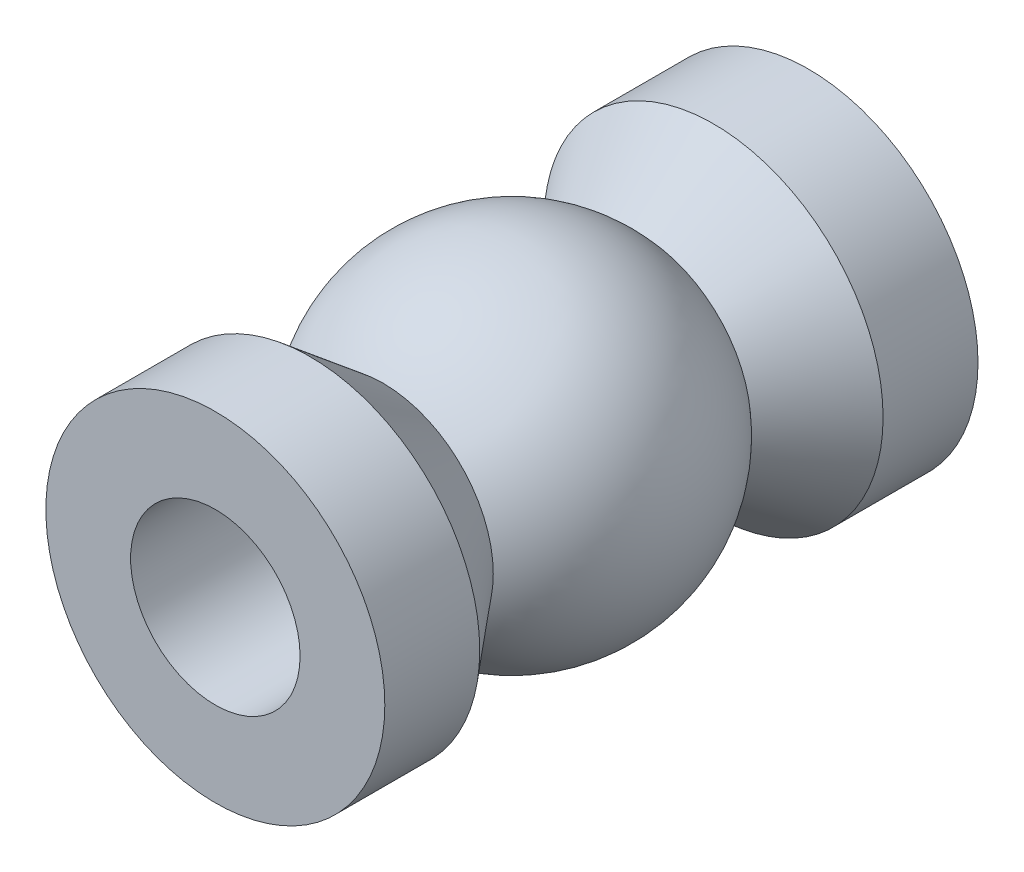
SolidWorks part; units mm, degrees
material "AISI 4130 Steel, normalized at 870C"
ref_plane "Front Plane" through (0, 0, 0) normal (0, 0, 1) x (1, 0, 0)
ref_plane "Top Plane" through (0, 0, 0) normal (0, 1, 0) x (1, 0, 0)
ref_plane "Right Plane" through (0, 0, 0) normal (1, 0, 0) x (0, 0, -1)
sketch "Sketch1" plane through (0, 0, 0) normal (1, 0, 0) x (0, 0, -1)
  line L0 (0.0693, 0) -> (6.3797, 0) construction
  line L1 (0, -3.9873) -> (0, 3.3979) construction
  line L2 (-11.1125, -3.175) -> (11.1125, -3.175)
  line L3 (11.1125, -3.175) -> (11.1125, -6.35)
  line L4 (11.1125, -6.35) -> (7.5565, -6.35)
  line L5 (7.5565, -6.35) -> (4.826, -4.127)
  line L6 (-11.1125, -3.175) -> (-11.1125, -6.35)
  line L7 (-11.1125, -6.35) -> (-7.5565, -6.35)
  line L8 (-7.5565, -6.35) -> (-4.826, -4.127)
  arc A0 (-4.826, -4.127) -> (4.826, -4.127) centre (0, 0) ccw
  point P12 (0, -3.175)
  point P22 (0, -6.35)
  dimension "D1" = 22.225
  dimension "D2" = 6.35
  dimension "D3" = 6.35
  dimension "D4" = 9.652
  dimension "D5" = 3.556
revolve "Revolve1" add sketch "Sketch1" angle 360 about L0
